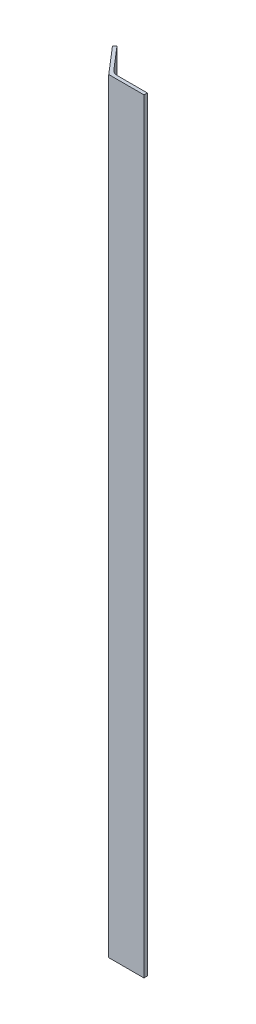
SolidWorks part; units mm, degrees
ref_plane "Спереди" through (0, 0, 0) normal (0, 0, 1) x (1, 0, 0)
ref_plane "Сверху" through (0, 0, 0) normal (0, 1, 0) x (1, 0, 0)
ref_plane "Справа" through (0, 0, 0) normal (1, 0, 0) x (0, 0, -1)
sketch "Эскиз1" plane through (0, 0, 0) normal (0, 1, 0) x (1, 0, 0)
  line L0 (-17.7667, 14.446) -> (-16.3084, 15.7)
  line L1 (-0.9318, 0.4869) -> (17.1228, 0.4869)
  line L2 (-16.3084, 15.7) -> (-4.7229, 2.2269)
  line L3 (-17.7667, 14.446) -> (-4.0435, -1.5131)
  line L4 (-4.0435, -1.5131) -> (17.1228, -1.5131)
  line L5 (17.1228, -1.5131) -> (17.1228, 0.4869)
  arc A0 (-0.9318, 0.4869) -> (-4.7229, 2.2269) centre (-0.9318, 5.4869) cw
  dimension "D1" = 5
extrude "Вытянуть1" add sketch "Эскиз1" along normal blind 460 from offset 40
sketch "Эскиз2" plane through (0, 0, 1.5131) normal (0, 0, 1) x (1, 0, 0)
  line L1 (21.3051, 405.4913) -> (7.411, 405.4913)
  line L2 (21.3051, 405.4913) -> (21.3051, 230.5293)
  line L3 (21.3051, 230.5293) -> (7.411, 230.5293)
  line L4 (7.411, 405.4913) -> (7.411, 230.5293)
extrude "Вырез-Вытянуть1" [suppressed] cut sketch "Эскиз2" against normal through all
